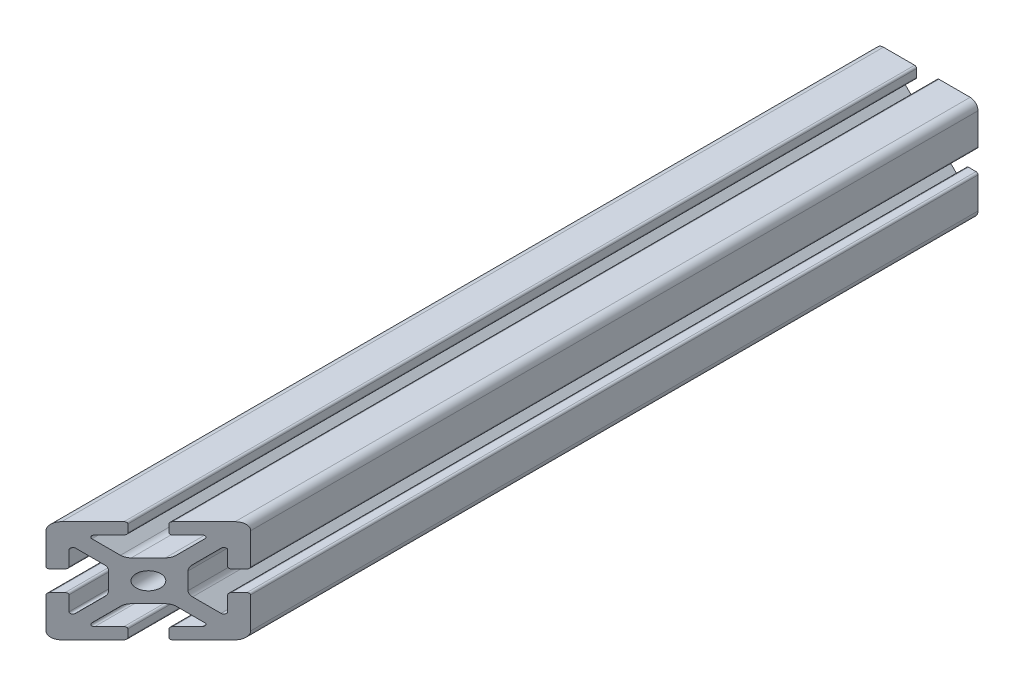
SolidWorks part; units mm, degrees
ref_plane "Front Plane" through (0, 0, 0) normal (0, 0, 1) x (1, 0, 0)
ref_plane "Top Plane" through (0, 0, 0) normal (0, 1, 0) x (1, 0, 0)
ref_plane "Right Plane" through (0, 0, 0) normal (1, 0, 0) x (0, 0, -1)
sketch "Sketch1" plane through (0, 0, 0) normal (0, 0, 1) x (1, 0, 0)
  line L0 (0, 20) -> (0, -20) construction
  line L1 (-20, 0) -> (20, 0) construction
  line L2 (-20, 16.952) -> (-20, 4.7625)
  line L3 (-16.952, 20) -> (-4.7625, 20)
  line L4 (-4.0005, 19.238) -> (-4.0005, 16.2662)
  line L5 (-4.7625, 15.5042) -> (-10.4856, 15.5042)
  line L6 (-11.0244, 14.2034) -> (-5.456, 8.6351)
  line L7 (-14.2034, 11.0244) -> (-8.6351, 5.456)
  line L8 (-15.5042, 10.4856) -> (-15.5042, 4.7625)
  line L9 (-16.2662, 4.0005) -> (-19.238, 4.0005)
  line L10 (0, 0) -> (-20, 20) construction
  line L11 (-3.3367, 7.7572) -> (3.3367, 7.7572)
  line L12 (-7.7572, 3.3367) -> (-7.7572, -3.3367)
  line L13 (16.2662, 4.0005) -> (19.238, 4.0005)
  line L14 (15.5042, 10.4856) -> (15.5042, 4.7625)
  line L15 (20, 16.952) -> (20, 4.7625)
  line L16 (16.952, 20) -> (4.7625, 20)
  line L17 (4.0005, 19.238) -> (4.0005, 16.2662)
  line L18 (4.7625, 15.5042) -> (10.4856, 15.5042)
  line L19 (7.7572, 3.3367) -> (7.7572, -3.3367)
  line L20 (11.0244, 14.2034) -> (5.456, 8.6351)
  line L21 (14.2034, 11.0244) -> (8.6351, 5.456)
  line L22 (-16.2662, -4.0005) -> (-19.238, -4.0005)
  line L23 (-15.5042, -10.4856) -> (-15.5042, -4.7625)
  line L24 (-14.2034, -11.0244) -> (-8.6351, -5.456)
  line L25 (-11.0244, -14.2034) -> (-5.456, -8.6351)
  line L26 (-4.7625, -15.5042) -> (-10.4856, -15.5042)
  line L27 (-4.0005, -19.238) -> (-4.0005, -16.2662)
  line L28 (-16.952, -20) -> (-4.7625, -20)
  line L29 (-20, -16.952) -> (-20, -4.7625)
  line L30 (20, -16.952) -> (20, -4.7625)
  line L31 (16.952, -20) -> (4.7625, -20)
  line L32 (4.0005, -19.238) -> (4.0005, -16.2662)
  line L33 (4.7625, -15.5042) -> (10.4856, -15.5042)
  line L34 (11.0244, -14.2034) -> (5.456, -8.6351)
  line L35 (14.2034, -11.0244) -> (8.6351, -5.456)
  line L36 (15.5042, -10.4856) -> (15.5042, -4.7625)
  line L37 (16.2662, -4.0005) -> (19.238, -4.0005)
  line L38 (-3.3367, -7.7572) -> (3.3367, -7.7572)
  circle A0 centre (0, 0) radius 3.4036
  arc A1 (-20, 16.952) -> (-16.952, 20) centre (-16.952, 16.952) cw
  arc A2 (-14.2034, 11.0244) -> (-15.5042, 10.4856) centre (-14.7422, 10.4856) ccw
  arc A3 (-10.4856, 15.5042) -> (-11.0244, 14.2034) centre (-10.4856, 14.7422) ccw
  arc A4 (-4.7625, 20) -> (-4.0005, 19.238) centre (-4.7625, 19.238) cw
  arc A5 (-20, 4.7625) -> (-19.238, 4.0005) centre (-19.238, 4.7625) ccw
  arc A6 (-15.5042, 4.7625) -> (-16.2662, 4.0005) centre (-16.2662, 4.7625) cw
  arc A7 (-4.0005, 16.2662) -> (-4.7625, 15.5042) centre (-4.7625, 16.2662) cw
  arc A8 (-3.3367, 7.7572) -> (-5.456, 8.6351) centre (-3.3367, 10.7544) cw
  arc A9 (-7.7572, 3.3367) -> (-8.6351, 5.456) centre (-10.7544, 3.3367) ccw
  arc A10 (15.5042, 4.7625) -> (16.2662, 4.0005) centre (16.2662, 4.7625) ccw
  arc A11 (20, 4.7625) -> (19.238, 4.0005) centre (19.238, 4.7625) cw
  arc A12 (20, 16.952) -> (16.952, 20) centre (16.952, 16.952) ccw
  arc A13 (4.7625, 20) -> (4.0005, 19.238) centre (4.7625, 19.238) ccw
  arc A14 (4.0005, 16.2662) -> (4.7625, 15.5042) centre (4.7625, 16.2662) ccw
  arc A15 (3.3367, 7.7572) -> (5.456, 8.6351) centre (3.3367, 10.7544) ccw
  arc A16 (7.7572, 3.3367) -> (8.6351, 5.456) centre (10.7544, 3.3367) cw
  arc A17 (14.2034, 11.0244) -> (15.5042, 10.4856) centre (14.7422, 10.4856) cw
  arc A18 (10.4856, 15.5042) -> (11.0244, 14.2034) centre (10.4856, 14.7422) cw
  arc A19 (-7.7572, -3.3367) -> (-8.6351, -5.456) centre (-10.7544, -3.3367) cw
  arc A20 (-3.3367, -7.7572) -> (-5.456, -8.6351) centre (-3.3367, -10.7544) ccw
  arc A21 (-4.0005, -16.2662) -> (-4.7625, -15.5042) centre (-4.7625, -16.2662) ccw
  arc A22 (-15.5042, -4.7625) -> (-16.2662, -4.0005) centre (-16.2662, -4.7625) ccw
  arc A23 (-20, -4.7625) -> (-19.238, -4.0005) centre (-19.238, -4.7625) cw
  arc A24 (-4.7625, -20) -> (-4.0005, -19.238) centre (-4.7625, -19.238) ccw
  arc A25 (-10.4856, -15.5042) -> (-11.0244, -14.2034) centre (-10.4856, -14.7422) cw
  arc A26 (-14.2034, -11.0244) -> (-15.5042, -10.4856) centre (-14.7422, -10.4856) cw
  arc A27 (-20, -16.952) -> (-16.952, -20) centre (-16.952, -16.952) ccw
  arc A28 (20, -16.952) -> (16.952, -20) centre (16.952, -16.952) cw
  arc A29 (14.2034, -11.0244) -> (15.5042, -10.4856) centre (14.7422, -10.4856) ccw
  arc A30 (10.4856, -15.5042) -> (11.0244, -14.2034) centre (10.4856, -14.7422) ccw
  arc A31 (4.7625, -20) -> (4.0005, -19.238) centre (4.7625, -19.238) cw
  arc A32 (20, -4.7625) -> (19.238, -4.0005) centre (19.238, -4.7625) ccw
  arc A33 (15.5042, -4.7625) -> (16.2662, -4.0005) centre (16.2662, -4.7625) cw
  arc A34 (4.0005, -16.2662) -> (4.7625, -15.5042) centre (4.7625, -16.2662) cw
  arc A35 (3.3367, -7.7572) -> (5.456, -8.6351) centre (3.3367, -10.7544) cw
  arc A36 (7.7572, -3.3367) -> (8.6351, -5.456) centre (10.7544, -3.3367) ccw
  point P29 (-20, 4.0005)
  point P32 (-15.5042, 4.0005)
  point P36 (-4.5782, 7.7572)
  point P68 (0, 7.7572)
  dimension "D4" = 6.8072
  dimension "D5" = 3.048
  dimension "D6" = 0.762
  dimension "D9" = 0.762
  dimension "D10" = 0.762
  dimension "D11" = 4.4958
  dimension "D13" = 2.9972
  dimension "D1" = 40
  dimension "D2" = 40
  dimension "D3" = 12.2428
  dimension "D7" = 8.001
  dimension "D8" = 4.4958
extrude "Extrude1" add sketch "Sketch1" along normal mid plane 381
ref_plane "Plane3" through (0, -16.952, 0) normal (0, -1, 0) x (-1, 0, 0)
sketch "Sketch6" plane through (0, -16.952, 0) normal (0, -1, 0) x (-1, 0, 0)
  line L0 (-20, -93.6943) -> (20, -133.6943)
  line L1 (-20, -190.5) -> (-20, 190.5) construction
  line L2 (20, -190.5) -> (20, 190.5) construction
  line L3 (20, -133.6943) -> (20, -190.5)
  line L4 (20, -190.5) -> (-20, -190.5)
  line L5 (-20, -190.5) -> (-20, -93.6943)
  line L7 (16.952, 190.5) -> (4.7625, 190.5) construction
  dimension "D1" = 45
  dimension "D2" = 324.1943
extrude "Cut-Extrude1" cut sketch "Sketch6" against normal up to surface (36.952 mm away) up to face at (-10.8573, 20, 0)
sketch "Sketch7" plane through (0, -16.952, 0) normal (0, 1, 0) x (1, 0, 0)
  line L0 (-20, -133.6943) -> (20, -93.6943)
  line L1 (20, -93.6943) -> (20, -190.5)
  line L2 (20, -190.5) -> (-20, -190.5)
  line L3 (-20, -190.5) -> (-20, -133.6943)
extrude "Cut-Extrude2" cut sketch "Sketch7" against normal up to surface (3.048 mm away) up to face at (-10.8573, -20, 0)
equation "\"D2@Sketch1\" = \"D1@Sketch1\""
